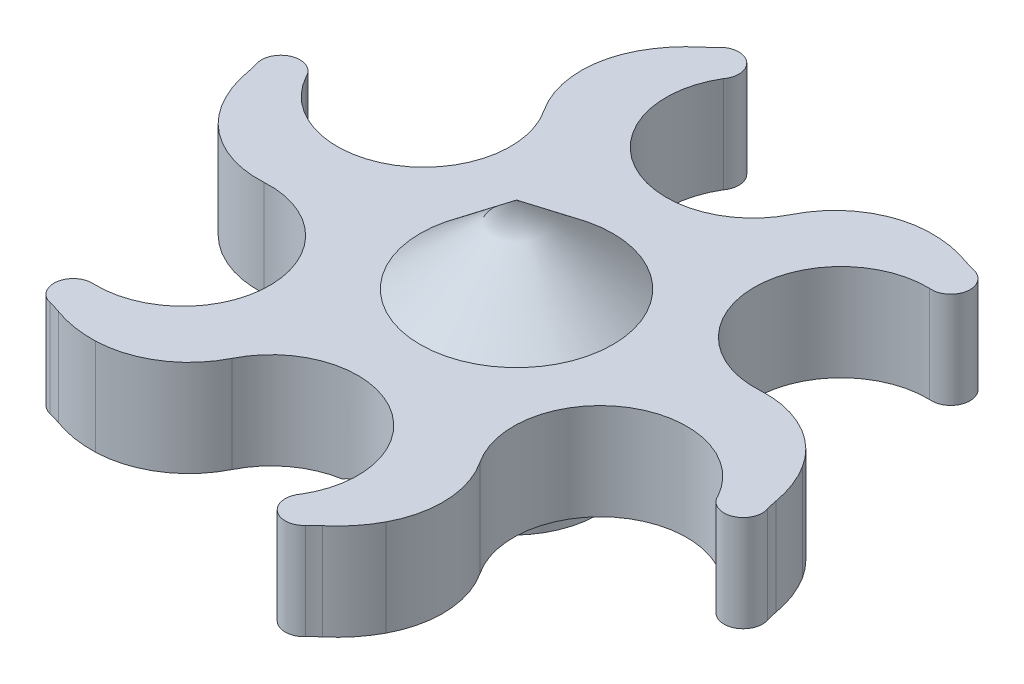
SolidWorks part; units mm, degrees
ref_plane "Front Plane" through (0, 0, 0) normal (0, 0, 1) x (1, 0, 0)
ref_plane "Top Plane" through (0, 0, 0) normal (0, 1, 0) x (1, 0, 0)
ref_plane "Right Plane" through (0, 0, 0) normal (1, 0, 0) x (0, 0, -1)
sketch "Sketch1" plane through (0, 0, 0) normal (0, 1, 0) x (1, 0, 0)
  circle A0 centre (0, 0) radius 9 construction
  arc A1 (-24.6742, 4.0231) -> (-24.6742, -4.0231) centre (0, 0) ccw
  arc A2 (-8.853, 23.38) -> (8.853, 23.38) centre (0, 25) ccw
  arc A3 (15.8212, 19.3569) -> (24.6742, 4.0231) centre (21.6506, 12.5) ccw
  arc A4 (24.6742, -4.0231) -> (15.8212, -19.3569) centre (21.6506, -12.5) ccw
  arc A5 (8.853, -23.38) -> (-8.853, -23.38) centre (0, -25) ccw
  arc A6 (-15.8212, -19.3569) -> (-24.6742, -4.0231) centre (-21.6506, -12.5) ccw
  arc A7 (-24.6742, 4.0231) -> (-15.8212, 19.3569) centre (-21.6506, 12.5) ccw
  arc A8 (-8.853, 23.38) -> (-15.8212, 19.3569) centre (0, 0) ccw
  arc A9 (15.8212, 19.3569) -> (8.853, 23.38) centre (0, 0) ccw
  arc A10 (24.6742, -4.0231) -> (24.6742, 4.0231) centre (0, 0) ccw
  arc A11 (8.853, -23.38) -> (15.8212, -19.3569) centre (0, 0) ccw
  arc A12 (-15.8212, -19.3569) -> (-8.853, -23.38) centre (0, 0) ccw
  point P18 (0, 0)
  dimension "D1" = 18
  dimension "D2" = 50
  dimension "D3" = 18
  dimension "D4" = 6
extrude "Boss-Extrude1" add sketch "Sketch1" along normal blind 10
sketch "Sketch2" plane through (0, 10, 0) normal (0, 1, 0) x (1, 0, 0)
  line L0 (0, 0) -> (-37.2267, 21.4929) construction
  line L1 (0, 0) -> (0, 42.8071) construction
  circle A0 centre (0, 25) radius 9 construction
  circle A1 centre (-21.6506, 12.5) radius 9 construction
  arc A2 (-15.8212, 19.3569) -> (-21.8212, 21.4984) centre (-21.6506, 12.5) ccw construction
  arc A3 (-22.0639, 25.4836) -> (-21.8212, 21.4984) centre (-22.0639, 23.4836) ccw construction
  arc A4 (-8.853, 23.38) -> (-22.0639, 25.4836) centre (-17.0842, 14.222) ccw construction
  arc A5 (-8.853, 23.38) -> (-15.8212, 19.3569) centre (0, 0) ccw construction
  arc A6 (-8.853, 23.38) -> (-15.8212, 19.3569) centre (0, 0) ccw construction
  arc A27 (8.853, 23.38) -> (22.0639, 25.4836) centre (17.0842, 14.222) cw
  arc A28 (22.0639, 25.4836) -> (21.8212, 21.4984) centre (22.0639, 23.4836) cw
  arc A29 (15.8212, 19.3569) -> (21.8212, 21.4984) centre (21.6506, 12.5) cw
  arc A30 (8.853, 23.38) -> (15.8212, 19.3569) centre (0, 0) cw
  arc A31 (24.6742, 4.0231) -> (33.1014, -6.3661) centre (20.8587, -7.6844) cw
  arc A32 (33.1014, -6.3661) -> (29.5287, -8.1485) centre (31.3693, -7.3661) cw
  arc A33 (24.6742, -4.0231) -> (29.5287, -8.1485) centre (21.6506, -12.5) cw
  arc A34 (24.6742, 4.0231) -> (24.6742, -4.0231) centre (0, 0) cw
  arc A35 (15.8212, -19.3569) -> (11.0375, -31.8497) centre (3.7745, -21.9063) cw
  arc A36 (11.0375, -31.8497) -> (7.7076, -29.6469) centre (9.3055, -30.8497) cw
  arc A37 (8.853, -23.38) -> (7.7076, -29.6469) centre (0, -25) cw
  arc A38 (15.8212, -19.3569) -> (8.853, -23.38) centre (0, 0) cw
  arc A39 (-8.853, -23.38) -> (-22.0639, -25.4836) centre (-17.0842, -14.222) cw
  arc A40 (-22.0639, -25.4836) -> (-21.8212, -21.4984) centre (-22.0639, -23.4836) cw
  arc A41 (-15.8212, -19.3569) -> (-21.8212, -21.4984) centre (-21.6506, -12.5) cw
  arc A42 (-8.853, -23.38) -> (-15.8212, -19.3569) centre (0, 0) cw
  arc A43 (-24.6742, -4.0231) -> (-33.1014, 6.3661) centre (-20.8587, 7.6844) cw
  arc A44 (-33.1014, 6.3661) -> (-29.5287, 8.1485) centre (-31.3693, 7.3661) cw
  arc A45 (-24.6742, 4.0231) -> (-29.5287, 8.1485) centre (-21.6506, 12.5) cw
  arc A46 (-24.6742, -4.0231) -> (-24.6742, 4.0231) centre (0, 0) cw
  arc A47 (-15.8212, 19.3569) -> (-11.0375, 31.8497) centre (-3.7745, 21.9063) cw
  arc A48 (-11.0375, 31.8497) -> (-7.7076, 29.6469) centre (-9.3055, 30.8497) cw
  arc A49 (-8.853, 23.38) -> (-7.7076, 29.6469) centre (0, 25) cw
  arc A50 (-15.8212, 19.3569) -> (-8.853, 23.38) centre (0, 0) cw
  point P26 (-11.9301, 29.6144)
  point P27 (-11.5373, 32.0063)
  point P55 (0, 0)
  point P63 (0, 0)
  point P64 (-10.624, 32.2585)
  point P65 (-11.0051, 31.8915)
  point P66 (-11.2381, 31.5217)
  point P67 (-10.7846, 32.1271)
  point P68 (-11.0375, 31.8497)
  dimension "D1" = 4
  dimension "D2" = 6
  dimension "D4" = 60
  dimension "D3" = 6
extrude "Boss-Extrude2" add sketch "Sketch2" against normal up to surface (10 mm away) up to face at (0, 0, 0)
fillet "Fillet1" radius 10 6 edges at (-24.6742, 5, 4.0231) (-8.853, 5, 23.38) (15.8212, 5, 19.3569) (24.6742, 5, -4.0231) (8.853, 5, -23.38) (-15.8212, 5, -19.3569)
sketch "Sketch3" plane through (0, 0, 0) normal (0, -1, 0) x (1, 0, 0)
  circle A0 centre (0, 0) radius 9 construction
  circle A1 centre (0, 0) radius 9
extrude "Boss-Extrude3" add sketch "Sketch3" along normal blind 6
sketch "Sketch5" plane through (0, 0, 0) normal (0, 0, 1) x (1, 0, 0)
  line L0 (-9, -6) -> (9, -6) construction
  circle A0 centre (0, -2.436) radius 1.65
  dimension "D1" = 3.3
  dimension "D2" = 3.564
extrude "Cut-Extrude1" cut sketch "Sketch5" against normal through all and the other way through all
sketch "Sketch6" plane through (0, 0, 0) normal (0, 0, 1) x (1, 0, 0)
  line L0 (0.4714, 10) -> (0.4714, 18)
  line L1 (9, 10) -> (-8.0572, 10) construction
  line L2 (0.4714, 18) -> (10.4714, 10)
  line L3 (10.4714, 10) -> (0.4714, 10)
  dimension "D1" = 10
  dimension "D2" = 8
revolve "Revolve1" add sketch "Sketch6" angle 360 about L0
ref_plane "Plane3" through (0, 0, 9) normal (0, 0, 1) x (1, 0, 0)
sketch "Sketch10" plane through (0, 0, 9) normal (0, 0, 1) x (1, 0, 0)
  circle A0 centre (0, -2.436) radius 2.85
  dimension "D1" = 5.7
extrude "Cut-Extrude4" cut sketch "Sketch10" along normal through all
mirror "Mirror1" about plane through (0, 0, 0) normal (0, 0, 1) of "Cut-Extrude4"
sketch "Sketch11" plane through (0, -6, 0) normal (0, -1, 0) x (1, 0, 0)
  line L0 (-1.8064, 2.55) -> (1.8064, 2.55)
  arc A0 (-1.8064, 2.55) -> (1.8064, 2.55) centre (0, 0) ccw
  dimension "D1" = 2.55
  dimension "D2" = 6.25
extrude "Cut-Extrude5" cut sketch "Sketch11" against normal blind 16
fillet "Fillet2" radius 10 6 edges at (-33.1014, 5, -6.3661) (-11.0375, 5, -31.8497) (22.0639, 5, -25.4836) (33.1014, 5, 6.3661) (11.0375, 5, 31.8497) (-22.0639, 5, 25.4836)
